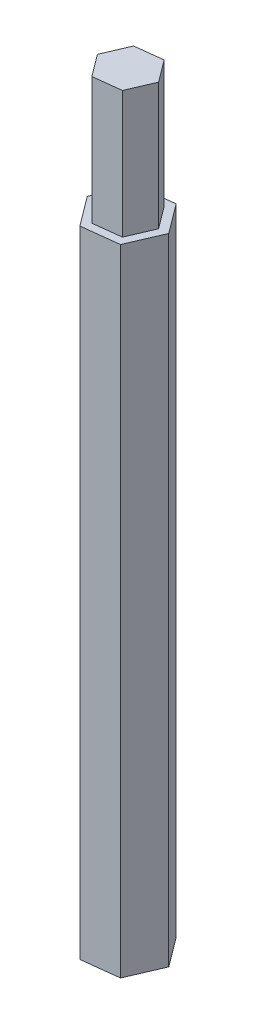
SolidWorks part; units mm, degrees
ref_plane "Front" through (0, 0, 0) normal (0, 0, 1) x (1, 0, 0)
ref_plane "Top" through (0, 0, 0) normal (0, 1, 0) x (1, 0, 0)
ref_plane "Right" through (0, 0, 0) normal (1, 0, 0) x (0, 0, -1)
sketch "Sketch1" plane through (0, 0, 0) normal (0, 1, 0) x (1, 0, 0)
  line L1 (4.3862, -5.8758) -> (7.2817, 0.8606)
  line L2 (7.2817, 0.8606) -> (2.8955, 6.7364)
  line L3 (2.8955, 6.7364) -> (-4.3862, 5.8758)
  line L4 (-4.3862, 5.8758) -> (-7.2817, -0.8606)
  line L5 (-7.2817, -0.8606) -> (-2.8955, -6.7364)
  line L6 (-2.8955, -6.7364) -> (4.3862, -5.8758)
  circle A0 centre (0, 0) radius 6.35 construction
  dimension "D1" = 12.7
extrude "Boss-Extrude1" add sketch "Sketch1" along normal blind 127
sketch "Sketch2" plane through (0, 127, 0) normal (0, 1, 0) x (1, 0, 0)
  line L0 (2.8955, 6.7364) -> (-4.3862, 5.8758) construction
  line L1 (5.4612, 0.6455) -> (2.1716, 5.0523)
  line L2 (2.1716, 5.0523) -> (-3.2896, 4.4068)
  line L3 (-3.2896, 4.4068) -> (-5.4612, -0.6455)
  line L4 (-5.4612, -0.6455) -> (-2.1716, -5.0523)
  line L5 (-2.1716, -5.0523) -> (3.2896, -4.4068)
  line L6 (3.2896, -4.4068) -> (5.4612, 0.6455)
  line L7 (7.2817, 0.8606) -> (2.8955, 6.7364) construction
  line L8 (-4.3862, 5.8758) -> (-7.2817, -0.8606) construction
  circle A0 centre (0, 0) radius 4.7625 construction
  point P10 (0, 0)
  point P11 (0, 0)
  point P12 (0, 0)
  point P13 (0, 0)
  dimension "D1" = 9.525
extrude "Boss-Extrude2" add sketch "Sketch2" along normal blind 25.4
